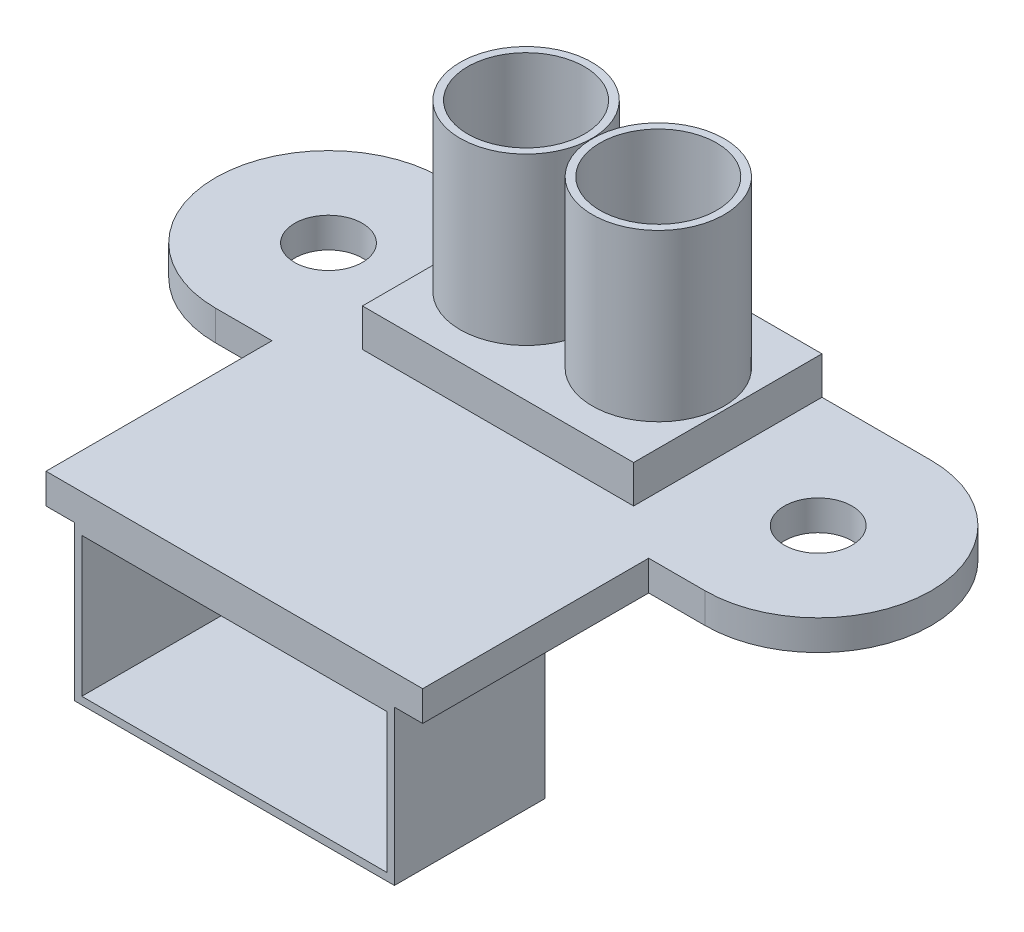
SolidWorks part; units mm, degrees
ref_plane "前视基准面" through (0, 0, 0) normal (0, 0, 1) x (1, 0, 0)
ref_plane "上视基准面" through (0, 0, 0) normal (0, 1, 0) x (1, 0, 0)
ref_plane "右视基准面" through (0, 0, 0) normal (1, 0, 0) x (0, 0, -1)
other "Configuration Table"
sketch "草图2" plane through (0, 0, 0) normal (0, 1, 0) x (1, 0, 0)
  line L0 (-6.5, 0) -> (6.5, 0) construction
  line L1 (-6.5, 3) -> (6.5, 3)
  line L2 (-6.5, -3) -> (-5, -3)
  line L3 (-5, -3) -> (-5, -9)
  line L4 (-5, -9) -> (5, -9)
  line L5 (5, -9) -> (5, -3)
  line L6 (0, -3) -> (0, 3) construction
  line L7 (5, -3) -> (6.5, -3)
  arc A0 (-6.5, 3) -> (-6.5, -3) centre (-6.5, 0) ccw
  arc A1 (6.5, -3) -> (6.5, 3) centre (6.5, 0) ccw
  circle A2 centre (-6.5, 0) radius 0.9
  circle A3 centre (6.5, 0) radius 0.9
  point P2 (0, 0)
  point P19 (0, 0)
  dimension "D3" = 1.8
  dimension "D4" = 1.8
  dimension "D1" = 6
  dimension "D2" = 13
  dimension "D5" = 12
  dimension "D6" = 10
extrude "凸台-拉伸1" add sketch "草图2" along normal blind 0.8
sketch "草图3" plane through (0, 0.8, 0) normal (0, 1, 0) x (1, 0, 0)
  line L0 (6.5, 3) -> (-6.5, 3) construction
  line L1 (-3.6, 3) -> (3.6, 3)
  line L2 (-3.6, 3) -> (-3.6, -2)
  line L3 (-3.6, -2) -> (3.6, -2)
  line L4 (3.6, 3) -> (3.6, -2)
  line L5 (-3.6, 3) -> (3.6, -2) construction
  line L6 (-3.6, -2) -> (3.6, 3) construction
  line L7 (0, -3) -> (0, 3) construction
  point P4 (0, 0.5)
  point P11 (0, 0)
  dimension "D1" = 7.2
  dimension "D2" = 5
extrude "凸台-拉伸2" add sketch "草图3" along normal blind 1
sketch "草图4" plane through (0, 1.8, 0) normal (0, 1, 0) x (1, 0, 0)
  line L0 (0, 3) -> (0, -2) construction
  line L1 (-3.6, 0.5) -> (3.6, 0.5) construction
  line L4 (-3.6, 3) -> (-3.6, -2)
  line L5 (-3.6, -2) -> (3.6, -2)
  line L6 (3.6, -2) -> (3.6, 3)
  line L7 (3.6, 3) -> (-3.6, 3)
  line L8 (-3.6, 3) -> (-3.6, -2) construction
  line L9 (-3.6, -2) -> (3.6, -2) construction
  line L10 (3.6, -2) -> (3.6, 3) construction
  line L11 (3.6, 3) -> (-3.6, 3) construction
  circle A0 centre (-1.755, 0.5) radius 1.75
  circle A1 centre (1.755, 0.5) radius 1.75
  circle A3 centre (1.755, 0.5) radius 1.55
  circle A4 centre (-1.755, 0.5) radius 1.55
  point P9 (0, 0.5)
  dimension "D2" = 3.5
  dimension "D4" = 0.01
  dimension "D1" = 0
  dimension "D3" = 0.2
extrude "凸台-拉伸5" add sketch "草图4" along normal blind 4.4
sketch "草图6" plane through (0, 0, 0) normal (0, -1, 0) x (1, 0, 0)
  line L0 (0, -9) -> (0, 9) construction
  line L1 (-5, 9) -> (5, 9) construction
  line L3 (-4.25, 9) -> (4.25, 9)
  line L4 (-4.25, 9) -> (-4.25, 5)
  line L5 (-4.25, 5) -> (4.25, 5)
  line L6 (4.25, 9) -> (4.25, 5)
  line L7 (-4.25, 9) -> (4.25, 5) construction
  line L8 (-4.25, 5) -> (4.25, 9) construction
  point P6 (0, 0)
  point P11 (0, 7)
  dimension "D1" = 8.5
  dimension "D2" = 4
extrude "凸台-拉伸6" add sketch "草图6" along normal blind 4.1
sketch "草图7" plane through (0, 0, 9) normal (0, 0, 1) x (1, 0, 0)
  line L0 (-4.05, -0.2) -> (4.05, -0.2)
  line L1 (-4.25, 0) -> (4.25, 0)
  line L2 (-4.25, 0) -> (-4.25, -4.1)
  line L3 (-4.25, -4.1) -> (4.25, -4.1)
  line L4 (4.25, 0) -> (4.25, -4.1)
  line L5 (-4.25, 0) -> (4.25, -4.1) construction
  line L6 (-4.25, -4.1) -> (4.25, 0) construction
  line L7 (4.05, -0.2) -> (4.05, -3.9)
  line L8 (-5, 0) -> (-4.25, 0)
  line L9 (-4.25, 0) -> (-4.25, -4.1)
  line L10 (-4.25, -4.1) -> (4.25, -4.1)
  line L11 (4.25, -4.1) -> (4.25, 0)
  line L12 (4.25, 0) -> (5, 0)
  line L13 (5, 0) -> (5, 0.8)
  line L14 (5, 0.8) -> (-5, 0.8)
  line L15 (-5, 0.8) -> (-5, 0)
  line L16 (-5, 0) -> (-4.25, 0) construction
  line L17 (-4.25, 0) -> (-4.25, -4.1) construction
  line L18 (-4.25, -4.1) -> (4.25, -4.1) construction
  line L19 (4.25, -4.1) -> (4.25, 0) construction
  line L20 (4.25, 0) -> (5, 0) construction
  line L21 (5, 0) -> (5, 0.8) construction
  line L22 (5, 0.8) -> (-5, 0.8) construction
  line L23 (-5, 0.8) -> (-5, 0) construction
  line L24 (-4.05, -3.9) -> (4.05, -3.9)
  line L25 (-4.05, -0.2) -> (-4.05, -3.9)
  point P4 (0, -2.05)
  dimension "D1" = 0
  dimension "D2" = 0.2
extrude "切除-拉伸1" cut sketch "草图7" against normal blind 3.8 contours L0 L25 L24 L7
